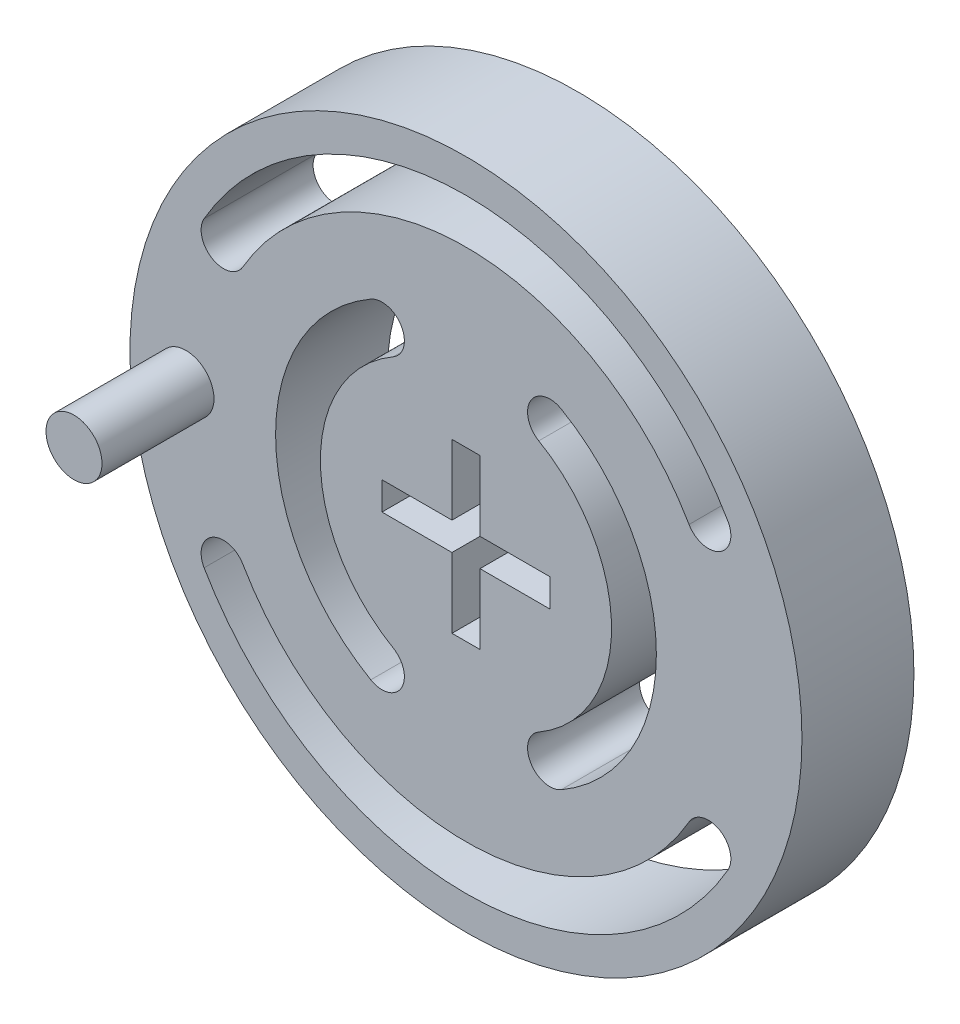
SolidWorks part; units mm, degrees
ref_plane "前视基准面" through (0, 0, 0) normal (0, 0, 1) x (1, 0, 0)
ref_plane "上视基准面" through (0, 0, 0) normal (0, 1, 0) x (1, 0, 0)
ref_plane "右视基准面" through (0, 0, 0) normal (1, 0, 0) x (0, 0, -1)
sketch "草图1" plane through (0, 0, 0) normal (0, 0, 1) x (1, 0, 0)
  circle A0 centre (0, 0) radius 30
  dimension "6" = 60
extrude "凸台-拉伸1" add sketch "草图1" along normal blind 10
sketch "草图2" plane through (0, 0, 10) normal (0, 0, 1) x (1, 0, 0)
  circle A0 centre (-25, 0) radius 2.5
  dimension "D1" = 5
  dimension "D2" = 25
extrude "凸台-拉伸3" add sketch "草图2" along normal blind 10
sketch "草图5" plane through (0, 0, 10) normal (0, 0, 1) x (1, 0, 0)
  line L1 (-1.25, 7.5) -> (1.25, 7.5)
  line L2 (-1.25, 7.5) -> (-1.25, -7.5)
  line L3 (-1.25, -7.5) -> (1.25, -7.5)
  line L4 (1.25, 7.5) -> (1.25, -7.5)
  line L5 (0, -7.5) -> (0, 7.5) construction
  line L6 (-1.25, 0) -> (1.25, 0) construction
  line L7 (-7.5, 1.25) -> (7.5, 1.25)
  line L8 (-7.5, 1.25) -> (-7.5, -1.25)
  line L9 (-7.5, -1.25) -> (7.5, -1.25)
  line L10 (7.5, 1.25) -> (7.5, -1.25)
  line L11 (0, -1.25) -> (0, 1.25) construction
  line L12 (-7.5, 0) -> (7.5, 0) construction
  point P0 (0, 0)
  point P5 (0, 0)
  dimension "D1" = 2.5
  dimension "D2" = 2.5
  dimension "D3" = 15
  dimension "D4" = 15
extrude "切除-拉伸3" cut sketch "草图5" against normal blind 10 contours L2 L7 L4 L1 | L8 L9 L2 L7 | L10 L7 L4 L9 | L9 L2 L3 L4 | L2 L9 L4 L7
sketch "草图7" plane through (0, 0, 10) normal (0, 0, 1) x (1, 0, 0)
  line L0 (0, 0) -> (-21.6506, 12.5) construction
  line L1 (0, 0) -> (21.6506, 12.5) construction
  line L2 (0, 0) -> (0, 11.9926) construction
  line L3 (0, 0) -> (-13.1774, 0) construction
  line L4 (0, 0) -> (-7.5, 12.9904) construction
  line L5 (0, 0) -> (-7.5, -12.9904) construction
  circle A0 centre (0, 0) radius 25 construction
  arc A1 (-21.6506, 12.5) -> (21.6506, 12.5) centre (0, 0) cw construction
  arc A2 (23.3827, 13.5) -> (-23.3827, 13.5) centre (0, 0) ccw
  arc A3 (19.9186, 11.5) -> (-19.9186, 11.5) centre (0, 0) ccw
  arc A4 (19.9186, 11.5) -> (23.3827, 13.5) centre (21.6506, 12.5) ccw
  arc A5 (-23.3827, 13.5) -> (-19.9186, 11.5) centre (-21.6506, 12.5) ccw
  arc A6 (-21.6506, -12.5) -> (21.6506, -12.5) centre (0, 0) ccw construction
  arc A7 (23.3827, -13.5) -> (-23.3827, -13.5) centre (0, 0) cw
  arc A8 (19.9186, -11.5) -> (-19.9186, -11.5) centre (0, 0) cw
  arc A9 (19.9186, -11.5) -> (23.3827, -13.5) centre (21.6506, -12.5) cw
  arc A10 (-23.3827, -13.5) -> (-19.9186, -11.5) centre (-21.6506, -12.5) cw
  circle A11 centre (0, 0) radius 15 construction
  arc A12 (-7.5, 12.9904) -> (-7.5, -12.9904) centre (0, 0) ccw construction
  arc A13 (-8.5, 14.7224) -> (-8.5, -14.7224) centre (0, 0) ccw
  arc A14 (-6.5, 11.2583) -> (-6.5, -11.2583) centre (0, 0) ccw
  arc A15 (-6.5, 11.2583) -> (-8.5, 14.7224) centre (-7.5, 12.9904) ccw
  arc A16 (-8.5, -14.7224) -> (-6.5, -11.2583) centre (-7.5, -12.9904) ccw
  arc A17 (7.5, 12.9904) -> (7.5, -12.9904) centre (0, 0) cw construction
  arc A18 (8.5, 14.7224) -> (8.5, -14.7224) centre (0, 0) cw
  arc A19 (6.5, 11.2583) -> (6.5, -11.2583) centre (0, 0) cw
  arc A20 (6.5, 11.2583) -> (8.5, 14.7224) centre (7.5, 12.9904) cw
  arc A21 (8.5, -14.7224) -> (6.5, -11.2583) centre (7.5, -12.9904) cw
  point P7 (0, 25)
  point P18 (0, -25)
  point P27 (-15, 0)
  point P36 (15, 0)
  dimension "D3" = 2
  dimension "D4" = 30
  dimension "D7" = 2
  dimension "D1" = 60
  dimension "D2" = 60
  dimension "D5" = 60
  dimension "D6" = 60
extrude "切除-拉伸4" cut sketch "草图7" against normal blind 20
